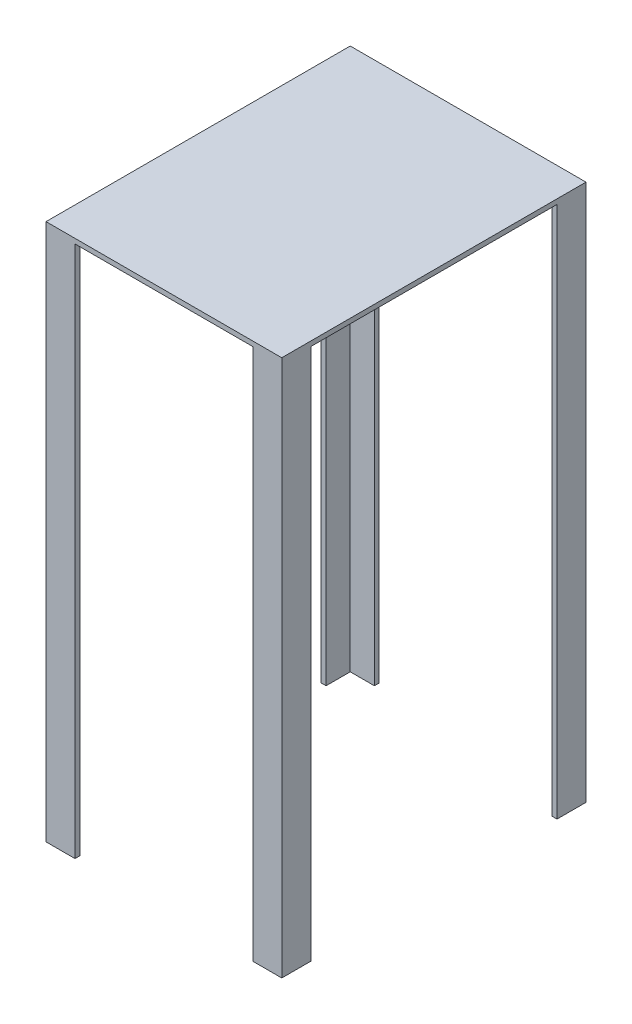
SolidWorks part; units mm, degrees
ref_plane "Alzado" through (0, 0, 0) normal (0, 0, 1) x (1, 0, 0)
ref_plane "Planta" through (0, 0, 0) normal (0, 1, 0) x (1, 0, 0)
ref_plane "Vista lateral" through (0, 0, 0) normal (1, 0, 0) x (0, 0, -1)
sketch "Croquis2" plane through (0, 0, 0) normal (0, 1, 0) x (1, 0, 0)
  line L1 (0, 0) -> (310, 0)
  line L2 (0, 0) -> (0, 400)
  line L3 (0, 400) -> (310, 400)
  line L4 (310, 0) -> (310, 400)
  dimension "D1" = 310
  dimension "D2" = 400
extrude "Saliente-Extruir1" add sketch "Croquis2" against normal blind 6.35
sketch "Croquis3" plane through (0, -6.35, 0) normal (0, -1, 0) x (1, 0, 0)
  line L0 (0, 0) -> (38.1, 0)
  line L1 (0, 0) -> (310, 0) construction
  line L2 (0, 0) -> (0, -38.1)
  line L3 (0, -400) -> (0, 0) construction
  line L4 (6.35, -6.35) -> (6.35, -38.1)
  line L5 (6.35, -6.35) -> (38.1, -6.35)
  line L6 (38.1, -6.35) -> (38.1, 0)
  line L7 (6.35, -38.1) -> (0, -38.1)
  line L8 (155, 0) -> (155, -200) construction
  line L9 (310, -200) -> (0, -200) construction
  line L10 (303.65, -38.1) -> (310, -38.1)
  line L11 (271.9, -6.35) -> (271.9, 0)
  line L12 (303.65, -6.35) -> (271.9, -6.35)
  line L13 (303.65, -6.35) -> (303.65, -38.1)
  line L14 (310, 0) -> (310, -38.1)
  line L15 (310, 0) -> (271.9, 0)
  line L16 (310, -400) -> (271.9, -400)
  line L17 (310, -400) -> (310, -361.9)
  line L18 (303.65, -393.65) -> (303.65, -361.9)
  line L19 (303.65, -393.65) -> (271.9, -393.65)
  line L20 (271.9, -393.65) -> (271.9, -400)
  line L21 (303.65, -361.9) -> (310, -361.9)
  line L22 (6.35, -361.9) -> (0, -361.9)
  line L23 (38.1, -393.65) -> (38.1, -400)
  line L24 (6.35, -393.65) -> (38.1, -393.65)
  line L25 (6.35, -393.65) -> (6.35, -361.9)
  line L26 (0, -400) -> (0, -361.9)
  line L27 (0, -400) -> (38.1, -400)
  dimension "D1" = 38.1
  dimension "D2" = 38.1
  dimension "D3" = 6.35
extrude "Saliente-Extruir2" add sketch "Croquis3" along normal blind 700
